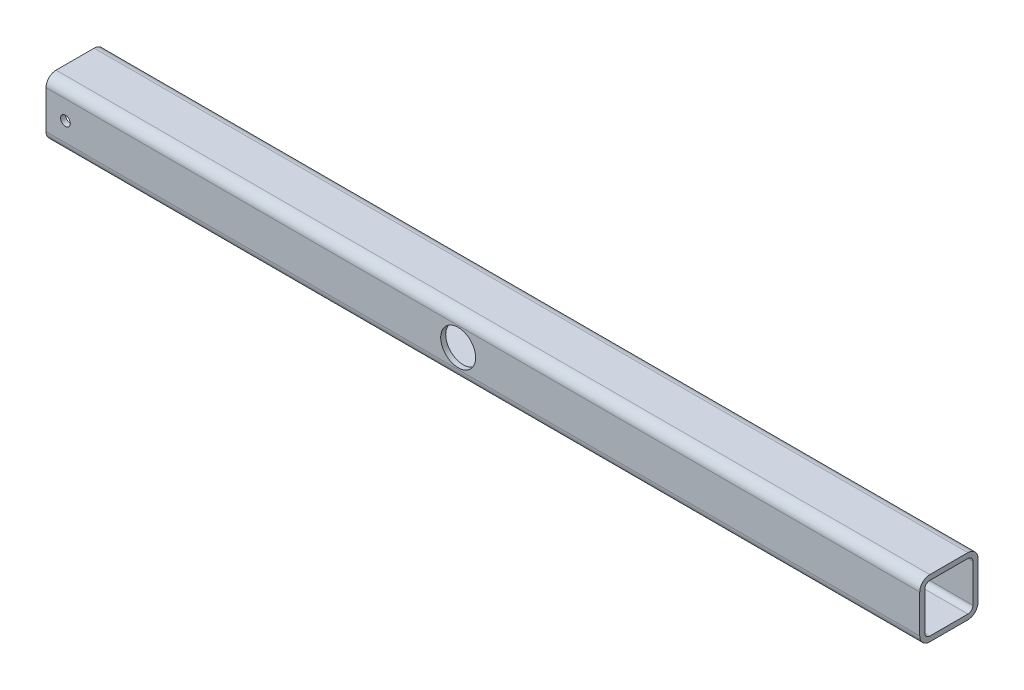
SolidWorks part; units mm, degrees
ref_plane "Płaszczyzna przednia" through (0, 0, 0) normal (0, 0, 1) x (1, 0, 0)
ref_plane "Płaszczyzna górna" through (0, 0, 0) normal (0, 1, 0) x (1, 0, 0)
ref_plane "Płaszczyzna prawa" through (0, 0, 0) normal (1, 0, 0) x (0, 0, -1)
sketch3d "Szkic 3D1"
  line L0 (-225, 0, 0) -> (225, 0, 0)
  dimension "D1" = 450
ref_plane "Płaszczyzna1" through (-225, 0, 0) normal (1, 0, 0) x (0, 0, -1)
other "Rura kwadratowa 30 X 30 X 2.6(1)"
ref_plane "Płaszczyzna2" through (-225, 0, 0) normal (1, 0, 0) x (0, 0, -1)
sketch "Sketch1" plane through (-225, 0, 0) normal (1, 0, 0) x (0, 0, -1)
  line L0 (-9.8, -12.4) -> (9.8, -12.4)
  line L1 (-12.4, -9.8) -> (-12.4, 9.8)
  line L2 (9.8, 12.4) -> (-9.8, 12.4)
  line L3 (12.4, 9.8) -> (12.4, -9.8)
  line L4 (-9.8, -15) -> (9.8, -15)
  line L5 (-15, -9.8) -> (-15, 9.8)
  line L6 (9.8, 15) -> (-9.8, 15)
  line L7 (15, 9.8) -> (15, -9.8)
  arc A0 (15, 9.8) -> (9.8, 15) centre (9.8, 9.8) ccw
  arc A1 (9.8, -15) -> (15, -9.8) centre (9.8, -9.8) ccw
  arc A2 (-15, -9.8) -> (-9.8, -15) centre (-9.8, -9.8) ccw
  arc A3 (-9.8, 15) -> (-15, 9.8) centre (-9.8, 9.8) ccw
  arc A4 (-9.8, 12.4) -> (-12.4, 9.8) centre (-9.8, 9.8) ccw
  arc A5 (12.4, 9.8) -> (9.8, 12.4) centre (9.8, 9.8) ccw
  arc A6 (9.8, -12.4) -> (12.4, -9.8) centre (9.8, -9.8) ccw
  arc A7 (-12.4, -9.8) -> (-9.8, -12.4) centre (-9.8, -9.8) ccw
  point P0 (-15, 0)
  point P1 (15, 0)
  point P2 (0, 15)
  point P3 (0, -15)
  point P4 (0, 0)
  point P5 (-15, -15)
  point P6 (15, -15)
  point P7 (15, 15)
  point P8 (-15, 15)
  point P33 (0, 0)
  dimension "D1" = 5.2
  dimension "Thickness" = 2.6
  dimension "V_leg" = 30
sketch "Szkic2" plane through (0, 0, 15) normal (0, 0, 1) x (1, 0, 0)
  line L0 (-225, 0) -> (225, 0) construction
  line L1 (-225, 9.8) -> (-225, -9.8) construction
  circle A0 centre (-215, 0) radius 2.5
  circle A1 centre (-12.73, 0) radius 9
  point P2 (0, 0)
  dimension "D1" = 5
  dimension "D3" = 18
  dimension "D2" = 10
  dimension "D4" = 202.27
extrude "Wytnij-wyciągnięcie1" cut sketch "Szkic2" against normal through all
